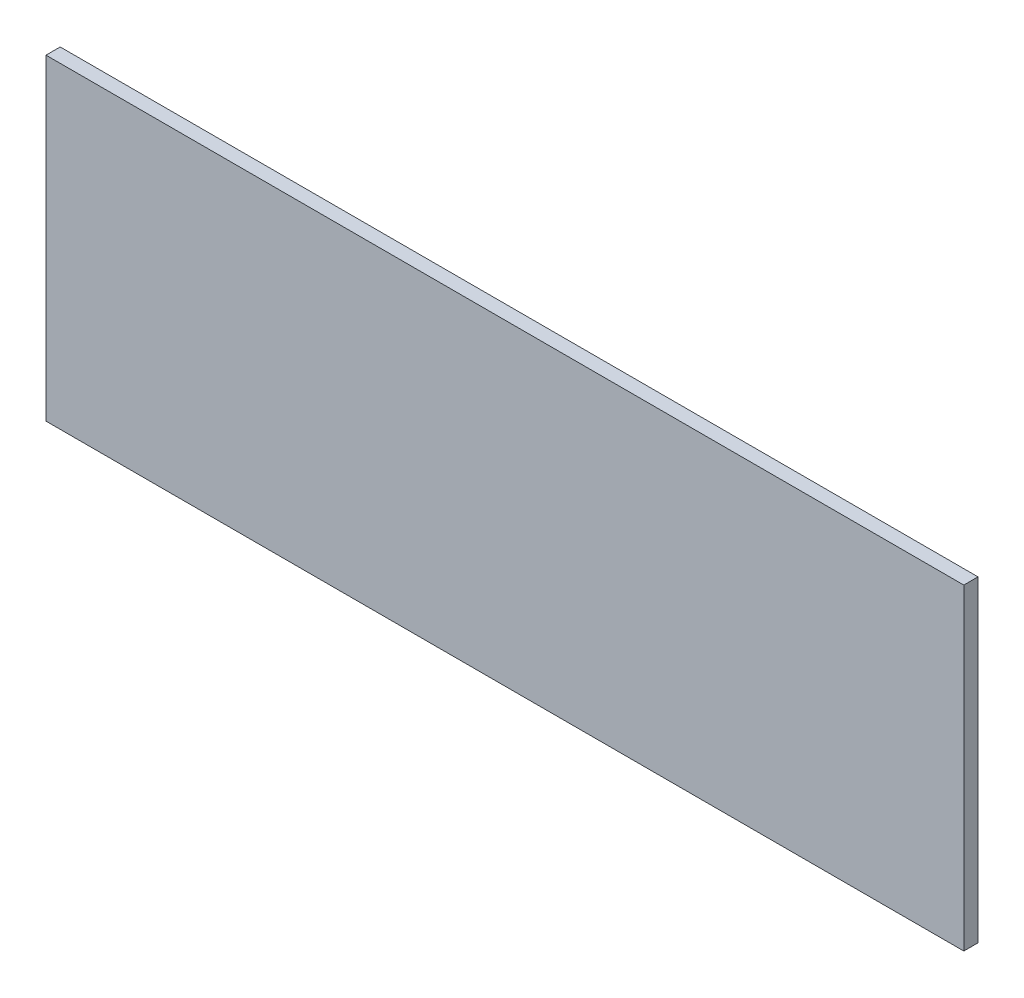
SolidWorks part; units mm, degrees
ref_plane "Front Plane" through (0, 0, 0) normal (0, 0, 1) x (1, 0, 0)
ref_plane "Top Plane" through (0, 0, 0) normal (0, 1, 0) x (1, 0, 0)
ref_plane "Right Plane" through (0, 0, 0) normal (1, 0, 0) x (0, 0, -1)
sketch "Sketch1" plane through (0, 0, 0) normal (0, 0, 1) x (1, 0, 0)
  line L1 (0, 0) -> (194, 0)
  line L2 (0, 0) -> (0, 67)
  line L3 (0, 67) -> (194, 67)
  line L4 (194, 0) -> (194, 67)
  dimension "D1" = 194
  dimension "D2" = 67
extrude "Profile" add sketch "Sketch1" along normal blind 3
equation "\"Profile_Depth\" = 3mm"
equation "\"D1@Profile\" = \"Profile_Depth\""
equation "\"EnvelopeWidth\" = 194mm"
equation "\"EnvelopeHeight\" = 67mm"
